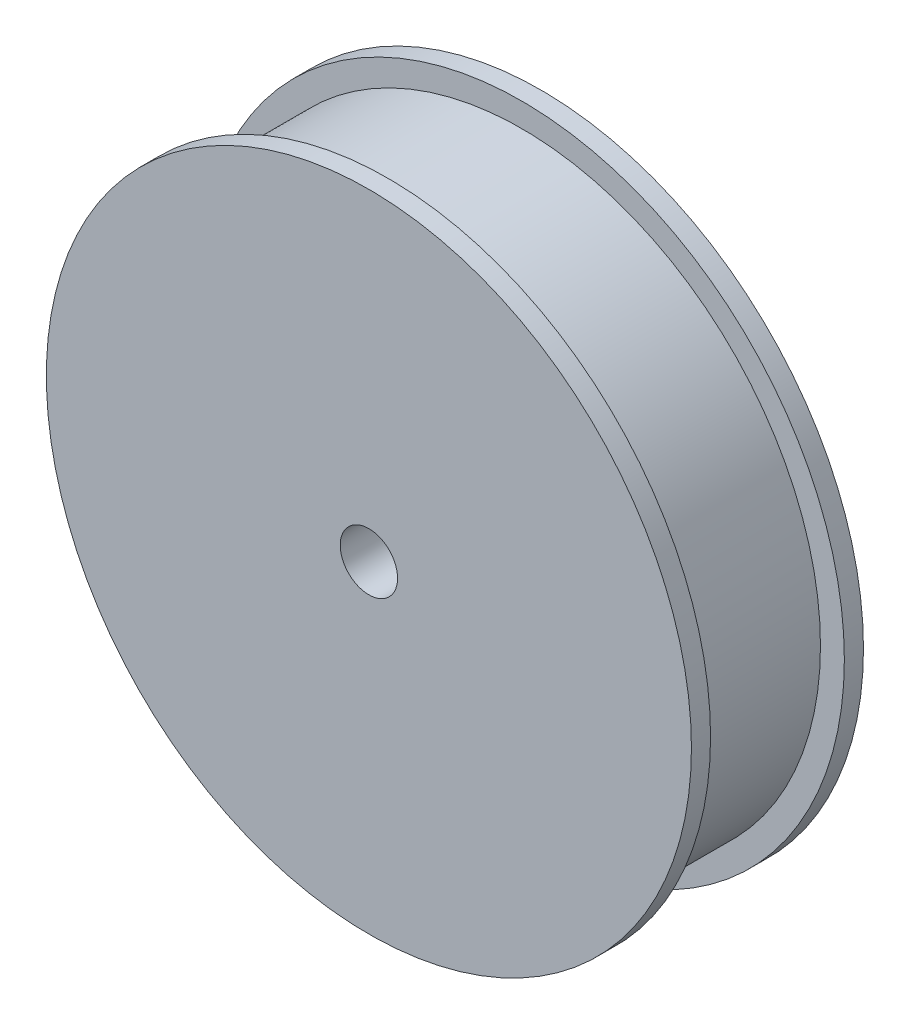
SolidWorks part; units mm, degrees
ref_plane "Front Plane" through (0, 0, 0) normal (0, 0, 1) x (1, 0, 0)
ref_plane "Top Plane" through (0, 0, 0) normal (0, 1, 0) x (1, 0, 0)
ref_plane "Right Plane" through (0, 0, 0) normal (1, 0, 0) x (0, 0, -1)
sketch "Sketch1" plane through (0, 0, 0) normal (0, 0, 1) x (1, 0, 0)
  circle A0 centre (0, 0) radius 31.25
  circle A1 centre (0, 0) radius 3
  dimension "D1" = 62.5
  dimension "D2" = 6
extrude "Boss-Extrude1" add sketch "Sketch1" along normal mid plane 16
sketch "Sketch2" plane through (0, 0, 8) normal (0, 0, 1) x (1, 0, 0)
  circle A0 centre (0, 0) radius 3
  circle A1 centre (0, 0) radius 33.75
  dimension "D1" = 67.5
  dimension "D2" = 6
extrude "Boss-Extrude2" add sketch "Sketch2" along normal mid plane 2
mirror "Mirror1" about plane through (0, 0, 0) normal (0, 0, 1) of "Boss-Extrude2"
